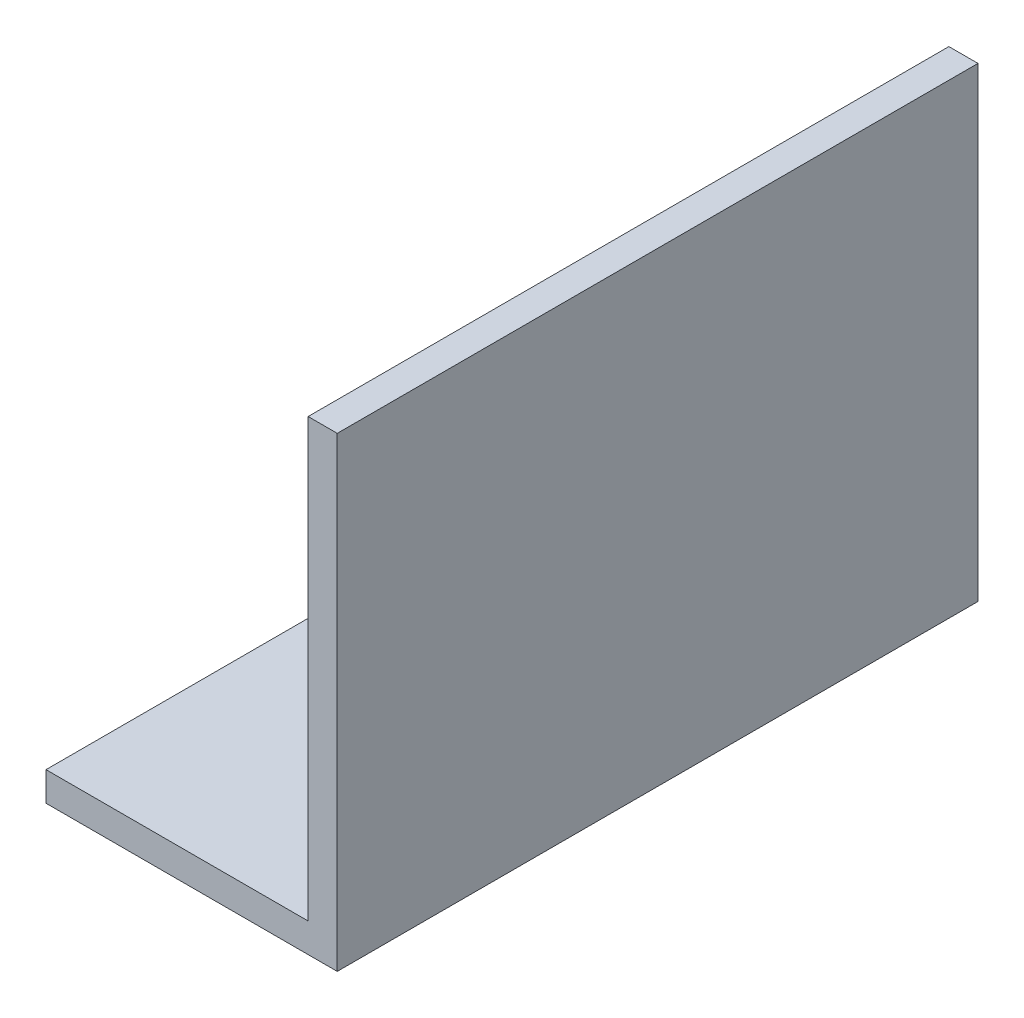
SolidWorks part; units mm, degrees
ref_plane "Front Plane" through (0, 0, 0) normal (0, 0, 1) x (1, 0, 0)
ref_plane "Top Plane" through (0, 0, 0) normal (0, 1, 0) x (1, 0, 0)
ref_plane "Right Plane" through (0, 0, 0) normal (1, 0, 0) x (0, 0, -1)
sketch "Sketch1" plane through (0, 0, 0) normal (0, 0, 1) x (1, 0, 0)
  line L0 (0, 0) -> (0, -80)
  line L6 (0, -80) -> (-50, -80)
  line L7 (-50, -80) -> (-50, -75)
  line L8 (-50, -75) -> (-5, -75)
  line L9 (-5, -75) -> (-5, 0)
  line L10 (-5, 0) -> (0, 0)
  dimension "D3" = 80
  dimension "D5" = 5
  dimension "D6" = 50
  dimension "D1" = 5
extrude "Boss-Extrude1" add sketch "Sketch1" along normal blind 110
equation "\"D1@Sketch1\"=\"D5@Sketch1\""
